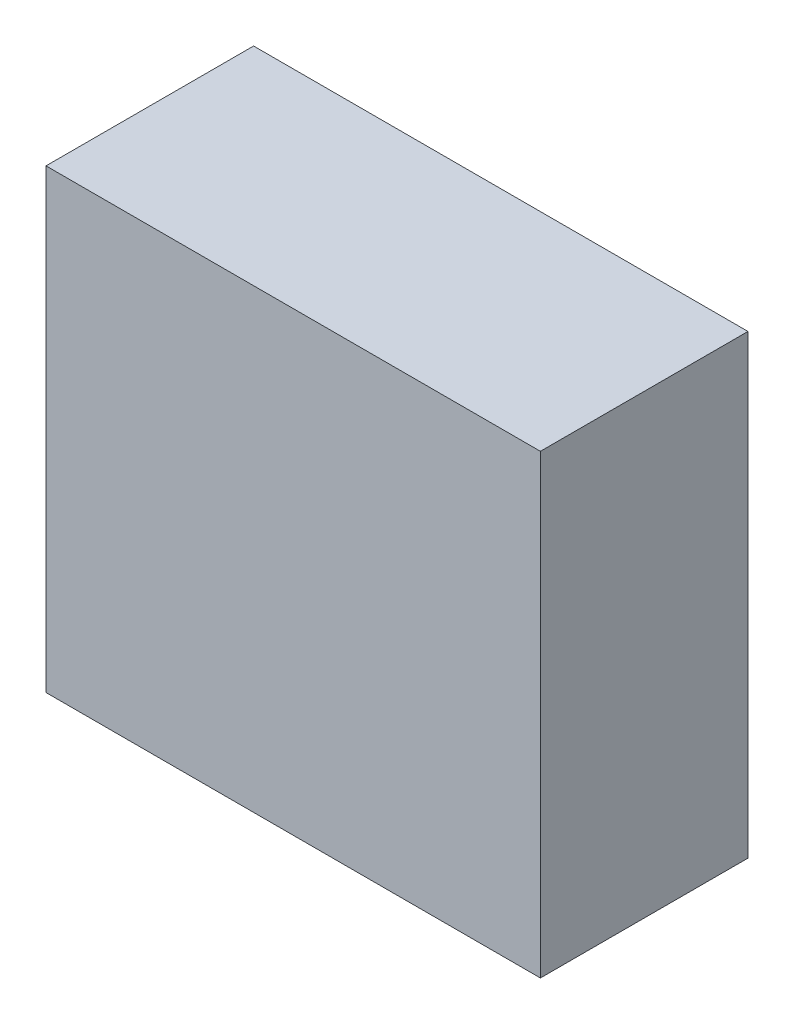
SolidWorks part; units mm, degrees
ref_plane "Front Plane" through (0, 0, 0) normal (0, 0, 1) x (1, 0, 0)
ref_plane "Top Plane" through (0, 0, 0) normal (0, 1, 0) x (1, 0, 0)
ref_plane "Right Plane" through (0, 0, 0) normal (1, 0, 0) x (0, 0, -1)
sketch "Sketch1" plane through (0, 0, 0) normal (0, 1, 0) x (1, 0, 0)
  line L1 (-90.5, -38) -> (90.5, -38)
  line L2 (-90.5, -38) -> (-90.5, 38)
  line L3 (-90.5, 38) -> (90.5, 38)
  line L4 (90.5, -38) -> (90.5, 38)
  line L5 (-90.5, -38) -> (90.5, 38) construction
  line L6 (-90.5, 38) -> (90.5, -38) construction
  point P0 (0, 0)
  dimension "D1" = 76
  dimension "D2" = 181
extrude "Boss-Extrude1" add sketch "Sketch1" along normal blind 167
